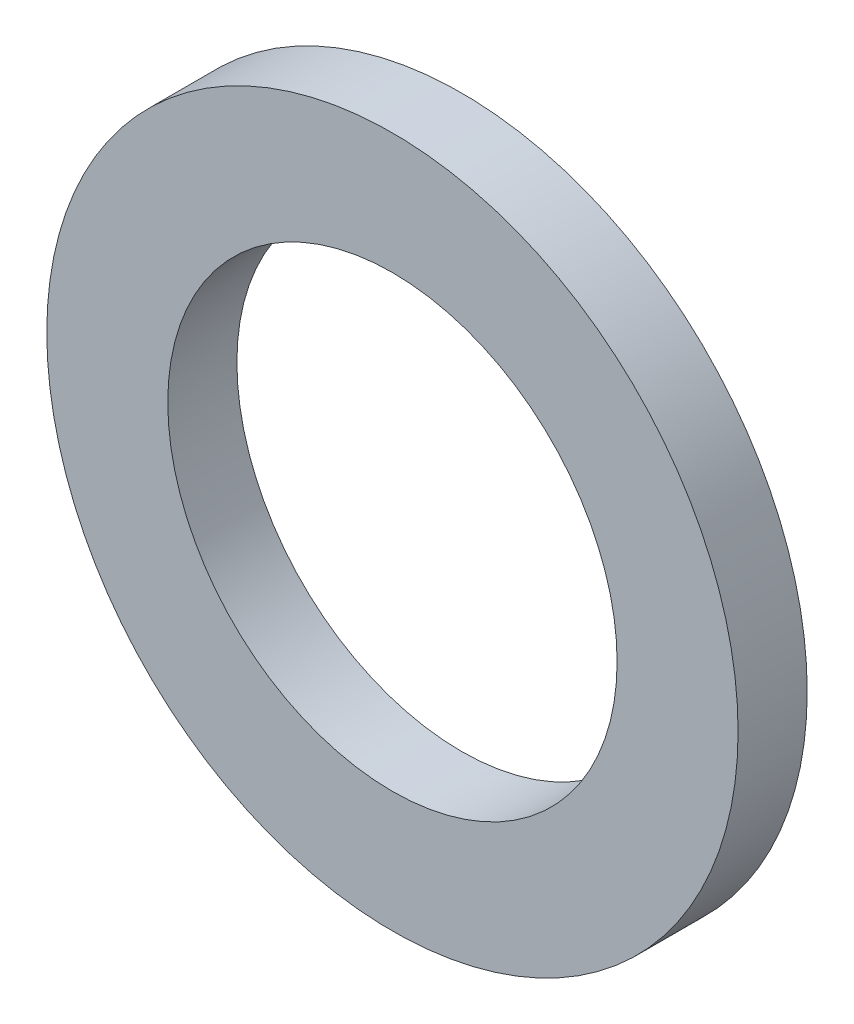
SolidWorks part; units mm, degrees
ref_plane "前基準面" through (0, 0, 0) normal (0, 0, 1) x (1, 0, 0)
ref_plane "上基準面" through (0, 0, 0) normal (0, 1, 0) x (1, 0, 0)
ref_plane "右基準面" through (0, 0, 0) normal (1, 0, 0) x (0, 0, -1)
sketch "草圖1" plane through (0, 0, 0) normal (0, 0, 1) x (1, 0, 0)
  circle A0 centre (0, 0) radius 3.25
  circle A1 centre (0, 0) radius 5
  dimension "D1" = 10
  dimension "D2" = 6.5
extrude "填料-伸長1" add sketch "草圖1" along normal blind 1
